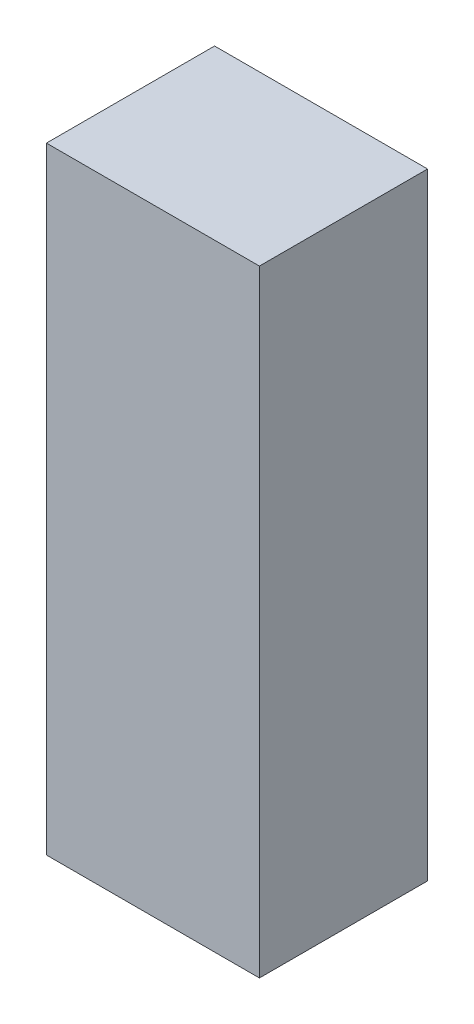
SolidWorks part; units mm, degrees
ref_plane "Front Plane" through (0, 0, 0) normal (0, 0, 1) x (1, 0, 0)
ref_plane "Top Plane" through (0, 0, 0) normal (0, 1, 0) x (1, 0, 0)
ref_plane "Right Plane" through (0, 0, 0) normal (1, 0, 0) x (0, 0, -1)
sketch "Sketch1" plane through (0, 0, 0) normal (0, 1, 0) x (1, 0, 0)
  line L1 (-47.5, 37.5) -> (47.5, 37.5)
  line L2 (-47.5, 37.5) -> (-47.5, -37.5)
  line L3 (-47.5, -37.5) -> (47.5, -37.5)
  line L4 (47.5, 37.5) -> (47.5, -37.5)
  line L5 (-47.5, 37.5) -> (47.5, -37.5) construction
  line L6 (-47.5, -37.5) -> (47.5, 37.5) construction
  point P0 (0, 0)
  dimension "D1" = 75
  dimension "D2" = 95
extrude "Boss-Extrude1" add sketch "Sketch1" along normal mid plane 275
